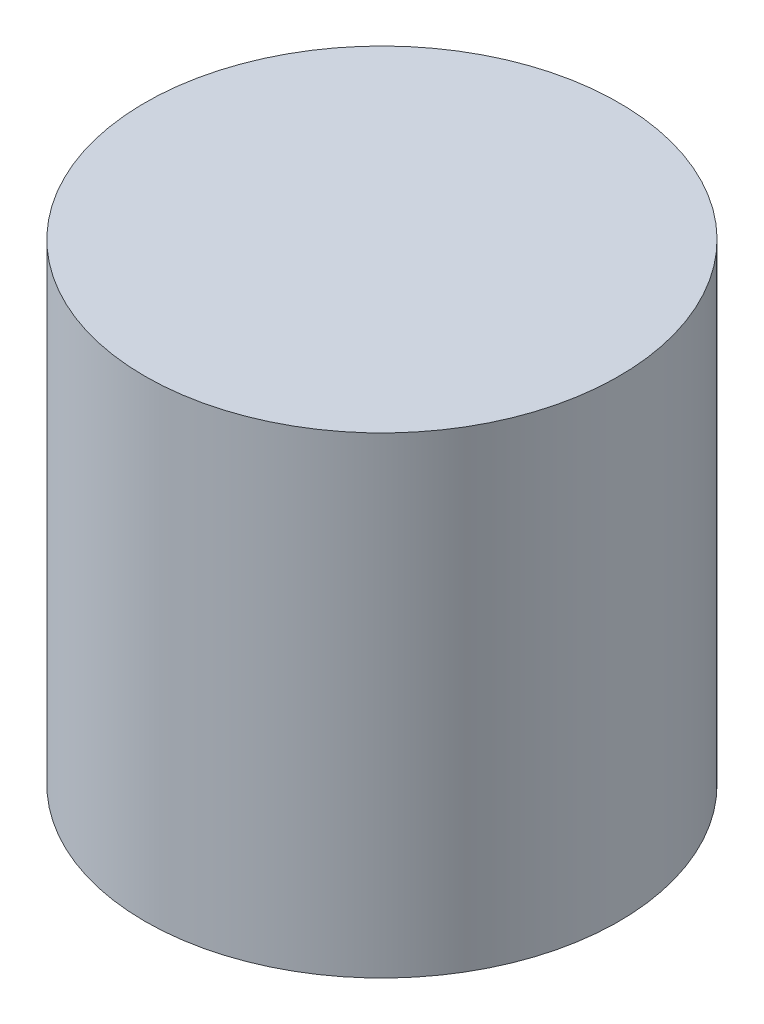
SolidWorks part; units mm, degrees
ref_plane "Front Plane" through (0, 0, 0) normal (0, 0, 1) x (1, 0, 0)
ref_plane "Top Plane" through (0, 0, 0) normal (0, 1, 0) x (1, 0, 0)
ref_plane "Right Plane" through (0, 0, 0) normal (1, 0, 0) x (0, 0, -1)
sketch "Sketch1" plane through (0, 0, 0) normal (0, 1, 0) x (1, 0, 0)
  circle A0 centre (0, 0) radius 5
  dimension "D1" = 10
extrude "Boss-Extrude1" add sketch "Sketch1" along normal blind 9.961
